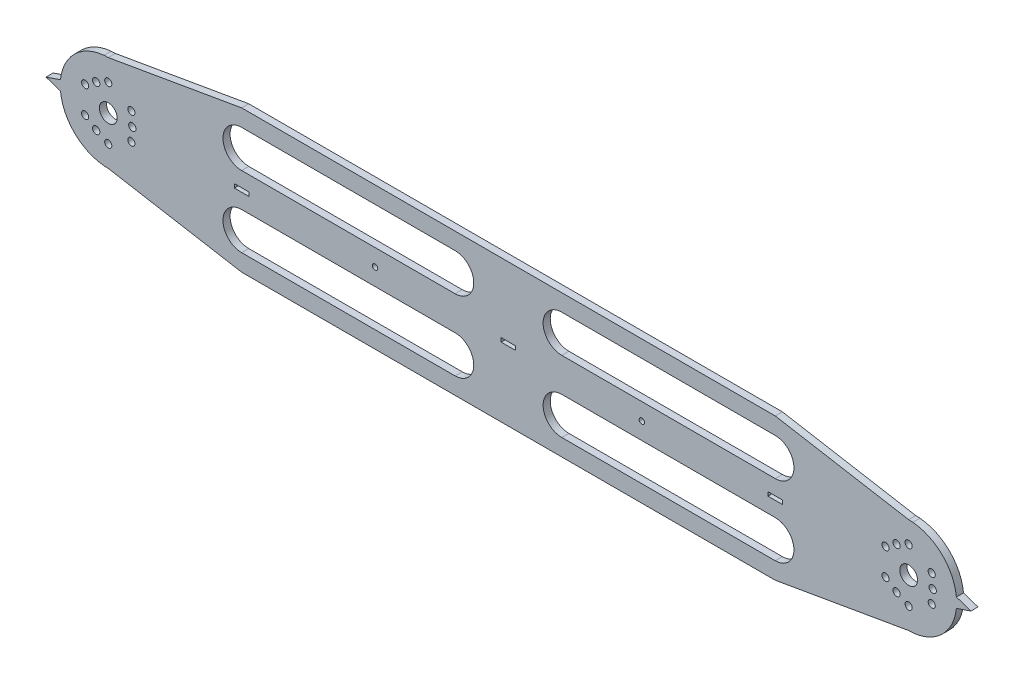
SolidWorks part; units mm, degrees
ref_plane "前视基准面" through (0, 0, 0) normal (0, 0, 1) x (1, 0, 0)
ref_plane "上视基准面" through (0, 0, 0) normal (0, 1, 0) x (1, 0, 0)
ref_plane "右视基准面" through (0, 0, 0) normal (1, 0, 0) x (0, 0, -1)
sketch "草图1" plane through (0, 0, 0) normal (0, 0, 1) x (1, 0, 0)
  line L0 (12.9904, 7.5) -> (12.9904, -7.5) construction
  line L1 (462.9904, 7.5) -> (462.9904, -7.5) construction
  line L2 (450, 0) -> (300, 0) construction
  line L3 (0, 0) -> (150, 0) construction
  line L4 (150, 0) -> (300, 0) construction
  line L5 (225, 0) -> (225, 4.9034) construction
  line L6 (375, 0) -> (375, 40) construction
  line L7 (220.9, -1.1) -> (229.1, -1.1)
  line L8 (220.9, -1.1) -> (220.9, 1.1)
  line L9 (220.9, 1.1) -> (229.1, 1.1)
  line L10 (229.1, -1.1) -> (229.1, 1.1)
  line L11 (220.9, -1.1) -> (229.1, 1.1) construction
  line L12 (220.9, 1.1) -> (229.1, -1.1) construction
  line L13 (79.1, 1.1) -> (70.9, 1.1)
  line L14 (79.1, 1.1) -> (79.1, -1.1)
  line L15 (79.1, -1.1) -> (70.9, -1.1)
  line L16 (70.9, 1.1) -> (70.9, -1.1)
  line L17 (79.1, 1.1) -> (70.9, -1.1) construction
  line L18 (79.1, -1.1) -> (70.9, 1.1) construction
  line L19 (379.1, 1.1) -> (370.9, 1.1)
  line L20 (379.1, 1.1) -> (379.1, -1.1)
  line L21 (379.1, -1.1) -> (370.9, -1.1)
  line L22 (370.9, 1.1) -> (370.9, -1.1)
  line L23 (379.1, 1.1) -> (370.9, -1.1) construction
  line L24 (379.1, -1.1) -> (370.9, 1.1) construction
  line L25 (375, 40) -> (450, 27)
  line L26 (375, 40) -> (75, 40)
  line L27 (75, 40) -> (0, 27)
  line L28 (75, -40) -> (0, -27)
  line L29 (375, -40) -> (450, -27)
  line L30 (375, -40) -> (75, -40)
  line L31 (375, 20) -> (75, 20) construction
  line L32 (75, 20) -> (195, 20) construction
  line L35 (75, 30.5) -> (195, 30.5)
  line L38 (75, 9.5) -> (195, 9.5)
  line L39 (375, 20) -> (255, 20) construction
  line L40 (375, 30.5) -> (255, 30.5)
  line L41 (375, 9.5) -> (255, 9.5)
  line L42 (75, -20) -> (195, -20) construction
  line L43 (75, -30.5) -> (195, -30.5)
  line L44 (75, -9.5) -> (195, -9.5)
  line L45 (375, -20) -> (255, -20) construction
  line L46 (375, -30.5) -> (255, -30.5)
  line L47 (375, -9.5) -> (255, -9.5)
  line L48 (0, 0) -> (-35, 0) construction
  line L63 (0, -27) -> (-2.3544, -26.8972)
  line L64 (450, -27) -> (452.3544, -26.8972)
  line L65 (452.3544, 26.8972) -> (450, 27)
  line L66 (-35, 0) -> (-12.9904, 7.5) construction
  line L70 (-26.857, 2.7748) -> (-35, 0)
  line L71 (-12.9904, -7.5) -> (-35, 0) construction
  line L72 (-35, 0) -> (-26.857, -2.7748)
  line L78 (476.857, -2.7748) -> (485, 0)
  line L79 (485, 0) -> (476.857, 2.7748)
  line L82 (0, 27) -> (-2.3544, 26.8972)
  circle A0 centre (0, 0) radius 15 construction
  circle A1 centre (0, -15) radius 2
  circle A2 centre (-12.9904, -7.5) radius 2
  circle A3 centre (-12.9904, 7.5) radius 2
  circle A4 centre (0, 15) radius 2
  circle A5 centre (12.9904, 7.5) radius 2
  circle A6 centre (12.9904, -7.5) radius 2
  circle A7 centre (0, 0) radius 13.53 construction
  circle A8 centre (13.53, 0) radius 2.05
  circle A9 centre (-6.765, -11.7173) radius 2.05
  circle A10 centre (-6.765, 11.7173) radius 2.05
  circle A11 centre (0, 0) radius 27 construction
  circle A12 centre (0, 0) radius 5
  circle A13 centre (450, 0) radius 15 construction
  circle A14 centre (450, -15) radius 2
  circle A15 centre (437.0096, -7.5) radius 2
  circle A16 centre (437.0096, 7.5) radius 2
  circle A17 centre (450, 15) radius 2
  circle A18 centre (462.9904, 7.5) radius 2
  circle A19 centre (462.9904, -7.5) radius 2
  circle A20 centre (450, 0) radius 13.53 construction
  circle A21 centre (463.53, 0) radius 2.05
  circle A22 centre (443.235, -11.7173) radius 2.05
  circle A23 centre (443.235, 11.7173) radius 2.05
  circle A25 centre (450, 0) radius 5
  circle A26 centre (300, 0) radius 1.5
  circle A27 centre (150, 0) radius 1.5
  arc A34 (75, 30.5) -> (75, 9.5) centre (75, 20) ccw
  arc A35 (195, 9.5) -> (195, 30.5) centre (195, 20) ccw
  arc A36 (375, 30.5) -> (375, 9.5) centre (375, 20) cw
  arc A37 (255, 9.5) -> (255, 30.5) centre (255, 20) cw
  arc A38 (75, -30.5) -> (75, -9.5) centre (75, -20) cw
  arc A39 (195, -9.5) -> (195, -30.5) centre (195, -20) cw
  arc A40 (375, -30.5) -> (375, -9.5) centre (375, -20) ccw
  arc A41 (255, -9.5) -> (255, -30.5) centre (255, -20) ccw
  arc A45 (-2.3544, 26.8972) -> (-26.857, 2.7748) centre (0, 0) ccw
  arc A46 (-2.3544, -26.8972) -> (-26.857, -2.7748) centre (0, 0) cw
  arc A47 (452.3544, -26.8972) -> (476.857, -2.7748) centre (450, 0) ccw
  arc A48 (452.3544, 26.8972) -> (476.857, 2.7748) centre (450, 0) cw
  point P57 (75, 0)
  point P62 (375, 0)
  point P77 (135, 20)
  point P85 (315, 20)
  point P92 (135, -20)
  point P99 (315, -20)
  point P111 (-27, 0)
  dimension "D1" = 6
  dimension "D2" = 3
extrude "凸台-拉伸1" add sketch "草图1" along normal blind 4
